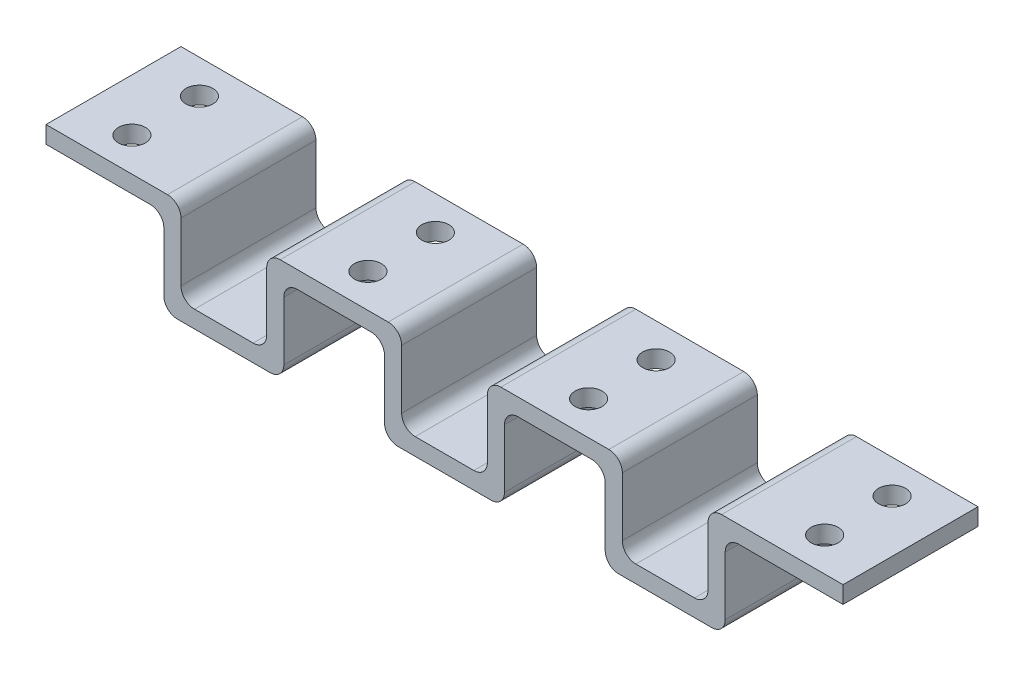
SolidWorks part; units mm, degrees
material "1023 Carbon Steel Sheet (SS)"
ref_plane "Front Plane" through (0, 0, 0) normal (0, 0, 1) x (1, 0, 0)
ref_plane "Top Plane" through (0, 0, 0) normal (0, 1, 0) x (1, 0, 0)
ref_plane "Right Plane" through (0, 0, 0) normal (1, 0, 0) x (0, 0, -1)
sketch "Sketch1" plane through (0, 0, 0) normal (0, 0, 1) x (1, 0, 0)
  line L0 (-23.3367, 0) -> (20.1633, 0)
  line L1 (-33.3367, 10) -> (-33.3367, 53.5)
  line L2 (30.1633, 10) -> (30.1633, 53.5)
  line L3 (40.1633, 63.5) -> (80.1633, 63.5)
  line L4 (-43.3367, 63.5) -> (-83.3367, 63.5)
  line L5 (-56.0367, 50.8) -> (-83.3367, 50.8)
  line L6 (-46.0367, -2.7) -> (-46.0367, 40.8)
  line L7 (-36.0367, -12.7) -> (32.8633, -12.7)
  line L8 (42.8633, -2.7) -> (42.8633, 40.8)
  line L9 (52.8633, 50.8) -> (80.1633, 50.8)
  line L10 (-83.3367, 81.1625) -> (-83.3367, 30.4327) construction
  line L11 (80.1633, 93.2259) -> (80.1633, 17.1313) construction
  line L12 (-206.8367, 63.5) -> (-296.8367, 63.5)
  line L13 (-296.8367, 63.5) -> (-296.8367, 50.8)
  line L14 (-209.5367, -2.7) -> (-209.5367, 40.8)
  line L15 (-130.6367, -12.7) -> (-199.5367, -12.7)
  line L16 (-120.6367, -2.7) -> (-120.6367, 40.8)
  line L17 (-110.6367, 50.8) -> (-83.3367, 50.8)
  line L18 (-123.3367, 63.5) -> (-83.3367, 63.5)
  line L19 (-296.8367, 50.8) -> (-219.5367, 50.8)
  line L20 (-196.8367, 10) -> (-196.8367, 53.5)
  line L21 (-133.3367, 10) -> (-133.3367, 53.5)
  line L22 (-143.3367, 0) -> (-186.8367, 0)
  line L23 (203.6633, 63.5) -> (293.6633, 63.5)
  line L24 (107.4633, 50.8) -> (80.1633, 50.8)
  line L25 (117.4633, -2.7) -> (117.4633, 40.8)
  line L26 (196.3633, -12.7) -> (127.4633, -12.7)
  line L27 (206.3633, -2.7) -> (206.3633, 40.8)
  line L28 (293.6633, 63.5) -> (293.6633, 50.8)
  line L29 (293.6633, 50.8) -> (216.3633, 50.8)
  line L30 (120.1633, 63.5) -> (80.1633, 63.5)
  line L31 (130.1633, 10) -> (130.1633, 53.5)
  line L32 (193.6633, 10) -> (193.6633, 53.5)
  line L33 (183.6633, 0) -> (140.1633, 0)
  line L34 (-46.0367, -12.7) -> (42.8633, -12.7) construction
  line L35 (42.8633, -12.7) -> (42.8633, 50.8) construction
  line L36 (-33.3367, 0) -> (30.1633, 0) construction
  line L37 (30.1633, 0) -> (30.1633, 63.5) construction
  line L38 (-33.3367, 0) -> (-33.3367, 63.5) construction
  line L39 (-46.0367, -12.7) -> (-46.0367, 50.8) construction
  line L40 (-33.3367, 63.5) -> (-83.3367, 63.5) construction
  line L41 (30.1633, 63.5) -> (80.1633, 63.5) construction
  line L42 (42.8633, 50.8) -> (80.1633, 50.8) construction
  line L43 (-46.0367, 50.8) -> (-83.3367, 50.8) construction
  arc A0 (183.6633, 0) -> (193.6633, 10) centre (183.6633, 10) ccw
  arc A1 (206.3633, -2.7) -> (196.3633, -12.7) centre (196.3633, -2.7) cw
  arc A2 (140.1633, 0) -> (130.1633, 10) centre (140.1633, 10) cw
  arc A3 (127.4633, -12.7) -> (117.4633, -2.7) centre (127.4633, -2.7) cw
  arc A4 (32.8633, -12.7) -> (42.8633, -2.7) centre (32.8633, -2.7) ccw
  arc A5 (20.1633, 0) -> (30.1633, 10) centre (20.1633, 10) ccw
  arc A6 (-23.3367, 0) -> (-33.3367, 10) centre (-23.3367, 10) cw
  arc A7 (-46.0367, -2.7) -> (-36.0367, -12.7) centre (-36.0367, -2.7) ccw
  arc A8 (-120.6367, -2.7) -> (-130.6367, -12.7) centre (-130.6367, -2.7) cw
  arc A9 (-143.3367, 0) -> (-133.3367, 10) centre (-143.3367, 10) ccw
  arc A10 (-186.8367, 0) -> (-196.8367, 10) centre (-186.8367, 10) cw
  arc A11 (-199.5367, -12.7) -> (-209.5367, -2.7) centre (-199.5367, -2.7) cw
  arc A12 (-196.8367, 53.5) -> (-206.8367, 63.5) centre (-206.8367, 53.5) ccw
  arc A13 (-133.3367, 53.5) -> (-123.3367, 63.5) centre (-123.3367, 53.5) cw
  arc A14 (-33.3367, 53.5) -> (-43.3367, 63.5) centre (-43.3367, 53.5) ccw
  arc A15 (30.1633, 53.5) -> (40.1633, 63.5) centre (40.1633, 53.5) cw
  arc A16 (130.1633, 53.5) -> (120.1633, 63.5) centre (120.1633, 53.5) ccw
  arc A17 (193.6633, 53.5) -> (203.6633, 63.5) centre (203.6633, 53.5) cw
  arc A18 (216.3633, 50.8) -> (206.3633, 40.8) centre (216.3633, 40.8) ccw
  arc A19 (117.4633, 40.8) -> (107.4633, 50.8) centre (107.4633, 40.8) ccw
  arc A20 (42.8633, 40.8) -> (52.8633, 50.8) centre (52.8633, 40.8) cw
  arc A21 (-56.0367, 50.8) -> (-46.0367, 40.8) centre (-56.0367, 40.8) cw
  arc A22 (-110.6367, 50.8) -> (-120.6367, 40.8) centre (-110.6367, 40.8) ccw
  arc A23 (-219.5367, 50.8) -> (-209.5367, 40.8) centre (-219.5367, 40.8) cw
  point P27 (193.6633, 0)
  point P38 (206.3633, -12.7)
  point P45 (130.1633, 0)
  point P48 (117.4633, -12.7)
  point P52 (42.8633, -12.7)
  point P56 (30.1633, 0)
  point P69 (-196.8367, 0)
  point P72 (-209.5367, -12.7)
  point P75 (-196.8367, 63.5)
  point P78 (-133.3367, 63.5)
  point P89 (193.6633, 63.5)
  point P92 (206.3633, 50.8)
  point P95 (117.4633, 50.8)
  dimension "D9" = 10
  dimension "D1" = 12.7
  dimension "D2" = 63.5
  dimension "D5" = 50
  dimension "D7" = 100
  dimension "D8" = 100
extrude "Boss-Extrude1" add sketch "Sketch1" along normal blind 100
sketch "Sketch2" plane through (0, 0, 0) normal (0, 1, 0) x (1, 0, 0)
  line L0 (-296.8367, -50) -> (293.6633, -50) construction
  line L1 (-296.8367, -100) -> (-296.8367, 0) construction
  line L2 (293.6633, -100) -> (293.6633, 0) construction
  line L3 (-83.3367, -100) -> (-83.3367, 0) construction
  line L6 (-83.3367, -100) -> (-83.3367, 0) construction
  line L7 (-110.6367, -100) -> (-56.0367, -100) construction
  line L8 (-110.6367, 0) -> (-56.0367, 0) construction
  line L9 (-258.1867, -100) -> (-258.1867, 0) construction
  line L10 (-296.8367, -100) -> (-219.5367, -100) construction
  line L11 (-296.8367, 0) -> (-219.5367, 0) construction
  line L12 (80.1633, -100) -> (80.1633, 0) construction
  line L13 (52.8633, -100) -> (107.4633, -100) construction
  line L14 (52.8633, 0) -> (107.4633, 0) construction
  line L15 (255.0133, -100) -> (255.0133, 0) construction
  line L16 (216.3633, -100) -> (293.6633, -100) construction
  line L17 (216.3633, 0) -> (293.6633, 0) construction
  line L18 (80.1633, -100) -> (80.1633, 0) construction
  line L19 (255.0133, -100) -> (255.0133, 0) construction
  line L20 (-1.5867, 5.8629) -> (-1.5867, -113.0406) construction
  circle A0 centre (-258.1867, -75) radius 10
  circle A1 centre (-258.1867, -25) radius 10
  circle A2 centre (-83.3367, -75) radius 10
  circle A3 centre (-83.3367, -25) radius 10
  circle A4 centre (80.1633, -75) radius 10
  circle A5 centre (80.1633, -25) radius 10
  circle A6 centre (255.0133, -75) radius 10
  circle A7 centre (255.0133, -25) radius 10
  dimension "D1" = 20
  dimension "D2" = 20
  dimension "D3" = 25
  dimension "D4" = 25
  dimension "D5" = 174.85
  dimension "D7" = 338.35
  dimension "D8" = 513.2
  dimension "D11" = 295.25
  dimension "D12" = 81.75
  dimension "D6" = 2
  dimension "D9" = 2
  dimension "D10" = 2
extrude "Cut-Extrude1" cut sketch "Sketch2" along normal blind 140.26
